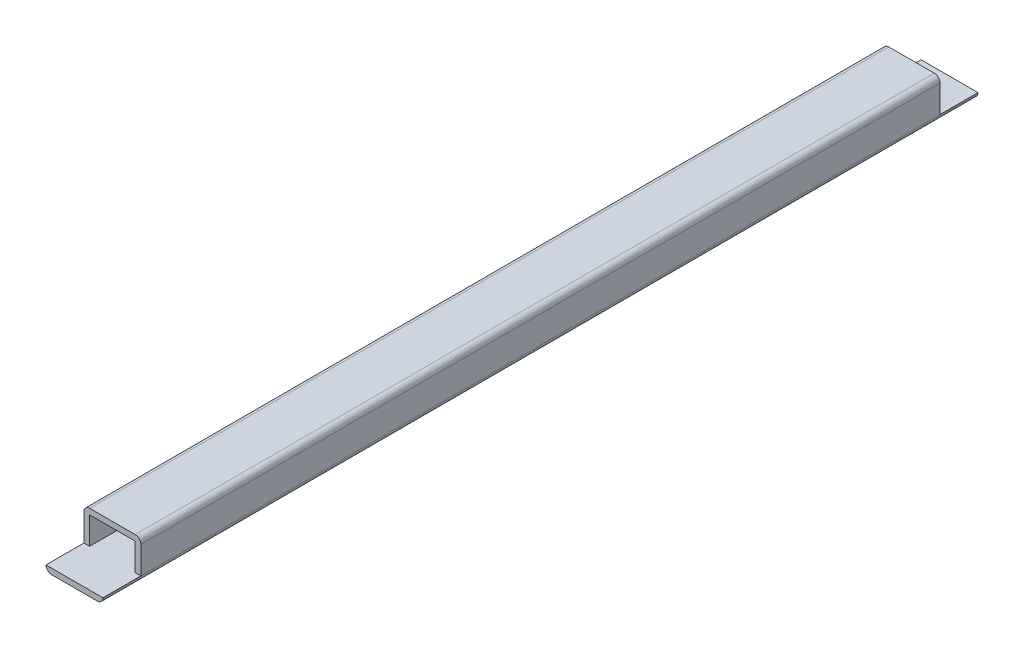
SolidWorks part; units mm, degrees
material "Gray Cast Iron"
ref_plane "Front Plane" through (0, 0, 0) normal (0, 0, 1) x (1, 0, 0)
ref_plane "Top Plane" through (0, 0, 0) normal (0, 1, 0) x (1, 0, 0)
ref_plane "Right Plane" through (0, 0, 0) normal (1, 0, 0) x (0, 0, -1)
sketch "Sketch1" plane through (0, 0, 0) normal (0, 0, 1) x (1, 0, 0)
  line L0 (3, 17.34) -> (27, 17.34)
  line L1 (3, 0) -> (27, 0)
  line L2 (0, 3) -> (0, 17.34)
  line L3 (3, 20.34) -> (27, 20.34)
  line L4 (30, 3) -> (30, 17.34)
  line L5 (27, 17.34) -> (27, 3)
  line L6 (27, 3) -> (3, 3)
  line L7 (3, 3) -> (3, 17.34)
  arc A0 (3, 20.34) -> (0, 17.34) centre (3, 17.34) ccw
  arc A1 (30, 17.34) -> (27, 20.34) centre (27, 17.34) ccw
  arc A2 (27, 0) -> (30, 3) centre (27, 3) ccw
  arc A3 (0, 3) -> (3, 0) centre (3, 3) ccw
  point P7 (0, 20.34)
  point P10 (30, 20.34)
  point P15 (0, 0)
  dimension "D3" = 3
  dimension "D4" = 3
  dimension "D5" = 3
  dimension "D6" = 3
  dimension "D1" = 20.34
  dimension "D2" = 30
extrude "Boss-Extrude1" add sketch "Sketch1" along normal blind 461
sketch "Sketch2" plane through (0, 0, 461) normal (0, 0, 1) x (1, 0, 0)
  line L0 (3, 3) -> (0, 3)
  line L1 (0, 3) -> (0, 17.34)
  line L2 (3, 20.34) -> (27, 20.34)
  line L3 (30, 17.34) -> (30, 3)
  line L4 (30, 3) -> (27, 3)
  line L5 (27, 3) -> (27, 17.34)
  line L6 (27, 17.34) -> (3, 17.34)
  line L7 (3, 17.34) -> (3, 3)
  arc A0 (0, 17.34) -> (3, 20.34) centre (3, 17.34) cw
  arc A1 (27, 20.34) -> (30, 17.34) centre (27, 17.34) cw
extrude "Cut-Extrude1" cut sketch "Sketch2" against normal blind 20
sketch "Sketch3" plane through (0, 0, 0) normal (0, 0, -1) x (-1, 0, 0)
  line L0 (-27, 3) -> (-27, 17.34)
  line L1 (-27, 17.34) -> (-3, 17.34)
  line L2 (-3, 17.34) -> (-3, 3)
  line L3 (-3, 3) -> (0, 3)
  line L4 (0, 3) -> (0, 17.34)
  line L5 (-3, 20.34) -> (-27, 20.34)
  line L6 (-30, 17.34) -> (-30, 3)
  line L7 (-30, 3) -> (-27, 3)
  arc A0 (0, 17.34) -> (-3, 20.34) centre (-3, 17.34) ccw
  arc A1 (-27, 20.34) -> (-30, 17.34) centre (-27, 17.34) ccw
extrude "Cut-Extrude2" cut sketch "Sketch3" against normal blind 20
